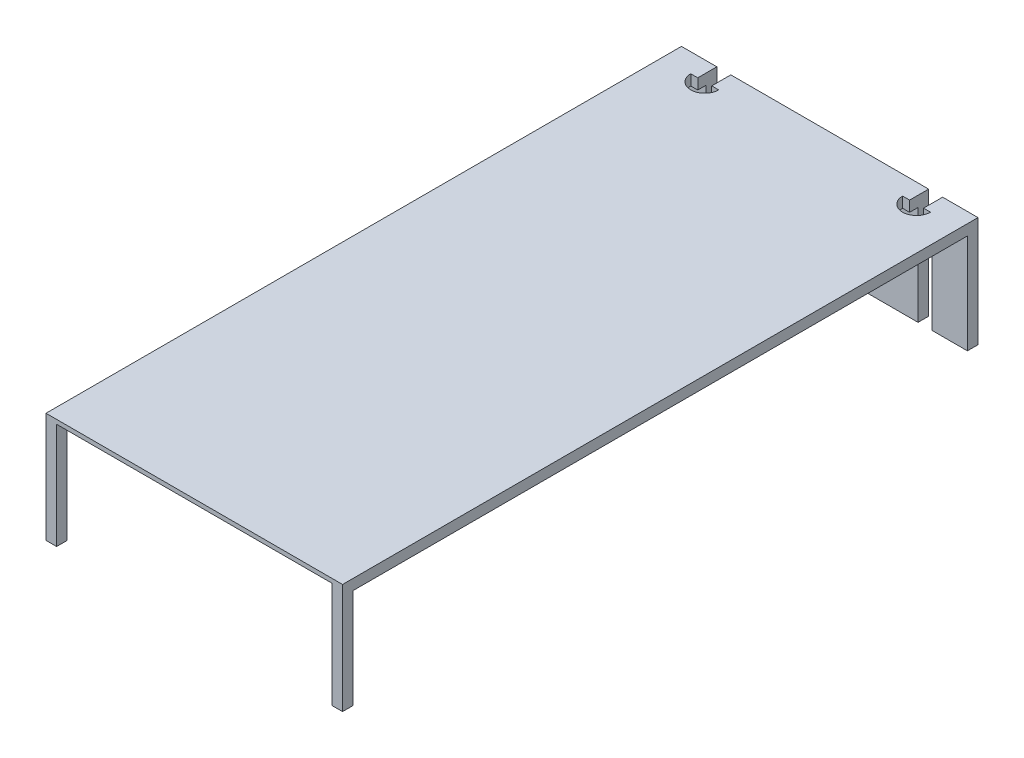
SolidWorks part; units mm, degrees
material "PVC 0.007 Plasticized"
ref_plane "Front Plane" through (0, 0, 0) normal (0, 0, 1) x (1, 0, 0)
ref_plane "Top Plane" through (0, 0, 0) normal (0, 1, 0) x (1, 0, 0)
ref_plane "Right Plane" through (0, 0, 0) normal (1, 0, 0) x (0, 0, -1)
sketch "Sketch2" plane through (0, 0, 0) normal (0, 1, 0) x (1, 0, 0)
  line L0 (-26.65, 75) -> (-26.65, 70.5)
  line L1 (-35, 75) -> (35, 75)
  line L2 (-35, 75) -> (-35, -75)
  line L3 (-35, -75) -> (35, -75)
  line L4 (35, 75) -> (35, -75)
  line L5 (0, -75) -> (0, 75) construction
  line L6 (-35, 0) -> (35, 0) construction
  line L7 (-26.65, 70.5) -> (-28.3, 70.5)
  line L8 (-21.7, 70.5) -> (-23.35, 70.5)
  line L9 (-23.35, 70.5) -> (-23.35, 75)
  line L10 (-23.35, 75) -> (-26.65, 75)
  line L11 (-25, 70.5) -> (-25, 75) construction
  line L12 (23.35, 70.5) -> (23.35, 75)
  line L13 (21.7, 70.5) -> (23.35, 70.5)
  line L14 (26.65, 70.5) -> (28.3, 70.5)
  line L15 (26.65, 75) -> (26.65, 70.5)
  line L16 (23.35, 75) -> (26.65, 75)
  arc A0 (-28.3, 70.5) -> (-21.7, 70.5) centre (-25, 70.5) ccw
  arc A1 (28.3, 70.5) -> (21.7, 70.5) centre (25, 70.5) cw
  point P344 (0, 0)
  dimension "D1" = 70
  dimension "D2" = 150
  dimension "D3" = 3.3
  dimension "D4" = 1.65
  dimension "D5" = 4.5
  dimension "D6" = 25
extrude "Boss-Extrude1" add sketch "Sketch2" along normal blind 26 contours L14 A1 L13 L12 L1 L9 L8 A0 L7 L0 L2 L3 L4 L15
sketch "Sketch3" plane through (35, 0, 0) normal (1, 0, 0) x (0, 0, -1)
  line L0 (75, 0) -> (-75, 0) construction
  line L1 (-72.5, 23.5) -> (72.5, 23.5)
  line L2 (-72.5, 23.5) -> (-72.5, 0)
  line L3 (-72.5, 0) -> (72.5, 0)
  line L4 (72.5, 23.5) -> (72.5, 0)
  line L5 (0, 0) -> (0, 23.5) construction
  line L6 (-72.5, 11.75) -> (72.5, 11.75) construction
  line L7 (75, 26) -> (75, 0) construction
  line L8 (-75, 26) -> (-75, 0) construction
  point P308 (0, 11.75)
  dimension "D1" = 2.5
  dimension "D2" = 2.5
  dimension "D3" = 23.5
extrude "Cut-Extrude1" cut sketch "Sketch3" against normal through all both and the other way through all
sketch "Sketch4" plane through (0, 0, 75) normal (0, 0, 1) x (1, 0, 0)
  line L0 (-35, 0) -> (35, 0) construction
  line L1 (-32.5, 25) -> (32.5, 25)
  line L2 (-32.5, 25) -> (-32.5, 0)
  line L3 (-32.5, 0) -> (32.5, 0)
  line L4 (32.5, 25) -> (32.5, 0)
  line L5 (0, 0) -> (0, 25) construction
  line L6 (-32.5, 12.5) -> (32.5, 12.5) construction
  line L7 (35, 26) -> (35, 0) construction
  line L8 (-35, 26) -> (-35, 0) construction
  point P436 (0, 12.5)
  dimension "D1" = 2.5
  dimension "D2" = 2.5
  dimension "D3" = 25
extrude "Cut-Extrude2" cut sketch "Sketch4" against normal blind 26 and the other way through all
